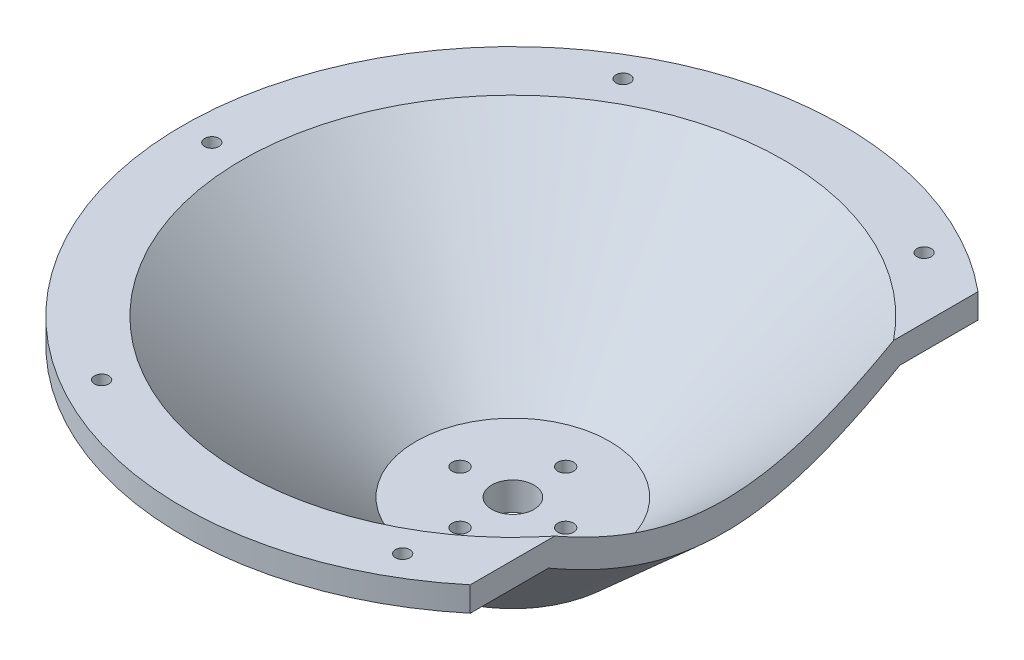
SolidWorks part; units mm, degrees
ref_plane "Front Plane" through (0, 0, 0) normal (0, 0, 1) x (1, 0, 0)
ref_plane "Top Plane" through (0, 0, 0) normal (0, 1, 0) x (1, 0, 0)
ref_plane "Right Plane" through (0, 0, 0) normal (1, 0, 0) x (0, 0, -1)
sketch "Sketch1" plane through (0, 0, 0) normal (0, 1, 0) x (1, 0, 0)
  circle A0 centre (0, 0) radius 27.5
  dimension "D1" = 55
extrude "Boss-Extrude1" add sketch "Sketch1" along normal blind 8
sketch "Sketch2" plane through (0, 8, 0) normal (0, 1, 0) x (1, 0, 0)
  circle A0 centre (0, 0) radius 15 construction
  point P3 (0, 15)
  dimension "D1" = 30
hole_wizard "M4 Clearance Hole1" positions "Sketch3" profile "Sketch4" hole size "M4" standard "ANSI Metric" end condition through all
sketch "Sketch3" plane through (0, 8, 0) normal (0, 1, 0) x (1, 0, 0)
  point P0 (0, 15)
sketch "Sketch4" plane through (0, 8, -15) normal (1, 0, 0) x (0, 0, 1)
  line L0 (0, 0) -> (0, 8)
  line L1 (0, 8) -> (2.25, 8)
  line L2 (2.25, 8) -> (2.25, 0)
  line L5 (2.25, 0) -> (0, 0)
  line L11 (0, -6.35) -> (0, 107.95) construction
  dimension "Thru Hole Dia." = 4.5
  dimension "Thru Hole Depth" = 8
pattern_circular "CirPattern1" count 4 over 360 about axis through (0, 0, 0) along (0, 1, 0) of "M4 Clearance Hole1"
sketch "Sketch6" plane through (0, 0, 0) normal (0, 0, 1) x (1, 0, 0)
  line L0 (17.5, 8) -> (17.5, 0)
  line L1 (27.5, 8) -> (-27.5, 8) construction
  line L2 (-27.5, 0) -> (27.5, 0) construction
  line L3 (17.5, 0) -> (27.5, 0)
  line L4 (27.5, 0) -> (85.8072, 52.5)
  line L5 (85.8072, 52.5) -> (76.9223, 52.5)
  line L6 (76.9223, 52.5) -> (27.5, 8)
  line L7 (27.5, 8) -> (17.5, 8)
  line L8 (27.5, 0) -> (27.5, 8) construction
  line L9 (78.0329, 45.5) -> (93.8072, 45.5)
  line L10 (93.8072, 45.5) -> (93.8072, 52.5)
  line L11 (93.8072, 52.5) -> (85.8072, 52.5)
  dimension "D1" = 42
  dimension "D2" = 10
  dimension "D3" = 44.5
  dimension "D4" = 8
  dimension "D5" = 7
ref_axis "Axis2" through (0, 8, 0) along (0, -1, 0)
revolve "Revolve1" add sketch "Sketch6" angle 360 about axis through (0, 8, 0) along (0, -1, 0)
sketch "Sketch8" plane through (0, 45.5, 0) normal (0, -1, 0) x (1, 0, 0)
  line L0 (0, 0) -> (85.5, 0) construction
  point P1 (85.5, 0)
  dimension "D1" = 85.5
sketch "Sketch11" plane through (0, 0, 0) normal (0, -1, 0) x (1, 0, 0)
  circle A0 centre (0, 0) radius 6
  dimension "D1" = 12
extrude "Cut-Extrude1" cut sketch "Sketch11" against normal through all
hole_wizard "CSK for #6 Flat Head Machine Screw1" positions "Sketch8" profile "Sketch13" countersink size "#6" standard "ANSI Inch" end condition through all
sketch "Sketch13" plane through (85.5, 45.5, 0) normal (1, 0, 0) x (0, 0, -1)
  line L0 (0, 0) -> (0, 7)
  line L1 (0, 7) -> (2.032, 7)
  line L2 (2.032, 7) -> (2.032, 1.8993)
  line L3 (2.032, 1.8993) -> (3.683, 0)
  line L5 (3.683, 0) -> (0, 0)
  line L6 (-2.032, 1.8993) -> (-3.683, 0) construction
  line L11 (0, -6.35) -> (0, 107.95) construction
  dimension "Thru Hole Dia." = 4.064
  dimension "Thru Hole Depth" = 7
  dimension "Near C'Sink Dia." = 7.366
  dimension "Near C'Sink Angle" = 82
pattern_circular "CirPattern2" count 6 over 360 about axis through (0, 0, 0) along (0, 1, 0) of "CSK for #6 Flat Head Machine Screw1"
ref_plane "Plane1" through (60, 0, 0) normal (1, 0, 0) x (0, 0, -1)
split "Split1" trim tools "Plane1" bodies to split 111 resulting bodies 113
